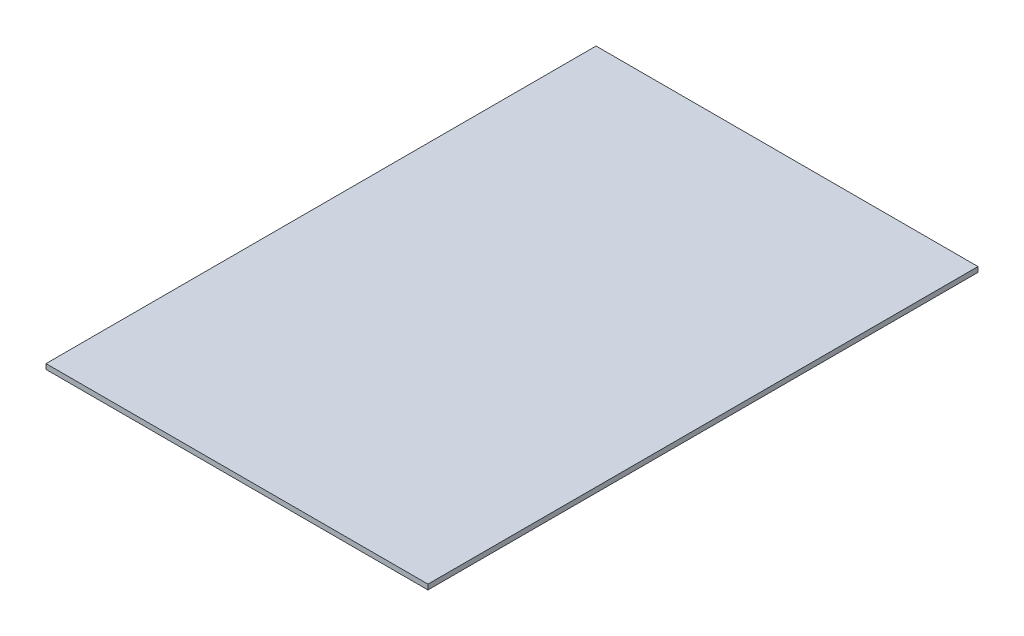
SolidWorks part; units mm, degrees
material "Oak"
ref_plane "Front Plane" through (0, 0, 0) normal (0, 0, 1) x (1, 0, 0)
ref_plane "Top Plane" through (0, 0, 0) normal (0, 1, 0) x (1, 0, 0)
ref_plane "Right Plane" through (0, 0, 0) normal (1, 0, 0) x (0, 0, -1)
sketch "Sketch1" plane through (0, 0, 0) normal (0, 1, 0) x (1, 0, 0)
  line L1 (-225.4, -324.6) -> (225.4, -324.6)
  line L2 (-225.4, -324.6) -> (-225.4, 324.6)
  line L3 (-225.4, 324.6) -> (225.4, 324.6)
  line L4 (225.4, -324.6) -> (225.4, 324.6)
  line L5 (-225.4, -324.6) -> (225.4, 324.6) construction
  line L6 (-225.4, 324.6) -> (225.4, -324.6) construction
  point P0 (0, 0)
  dimension "D1" = 450.8
  dimension "D2" = 649.2
extrude "Boss-Extrude1" add sketch "Sketch1" along normal blind 6
